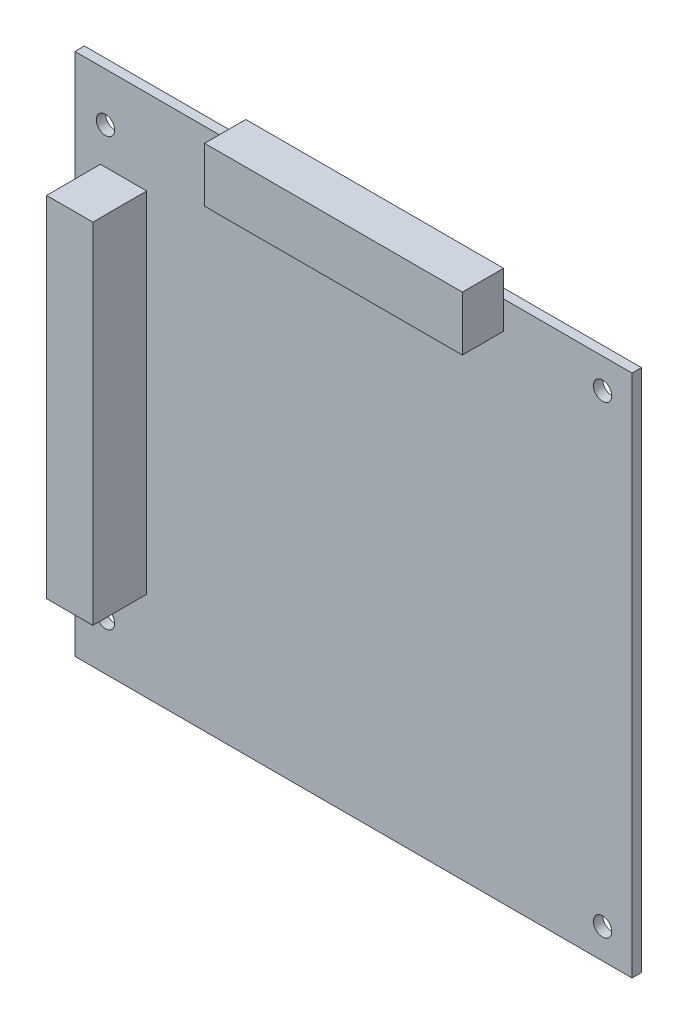
SolidWorks part; units mm, degrees
ref_plane "Front Plane" through (0, 0, 0) normal (0, 0, 1) x (1, 0, 0)
ref_plane "Top Plane" through (0, 0, 0) normal (0, 1, 0) x (1, 0, 0)
ref_plane "Right Plane" through (0, 0, 0) normal (1, 0, 0) x (0, 0, -1)
sketch "Sketch1" plane through (0, 0, 0) normal (0, 0, 1) x (1, 0, 0)
  line L1 (-48.0314, -45.1739) -> (48.0314, -45.1739)
  line L2 (-48.0314, -45.1739) -> (-48.0314, 45.1739)
  line L3 (-48.0314, 45.1739) -> (48.0314, 45.1739)
  line L4 (48.0314, -45.1739) -> (48.0314, 45.1739)
  line L5 (-48.0314, -45.1739) -> (48.0314, 45.1739) construction
  line L6 (-48.0314, 45.1739) -> (48.0314, -45.1739) construction
  point P0 (0, 0)
  dimension "D1" = 96.0628
  dimension "D2" = 90.3478
extrude "PCB" add sketch "Sketch1" along normal blind 1.6256
sketch "Sketch5" plane through (0, 0, 1.6256) normal (0, 0, 1) x (1, 0, 0)
  line L0 (-42.7736, 45.1739) -> (-42.7736, 36.83) construction
  line L1 (48.0314, 45.1739) -> (-48.0314, 45.1739) construction
  line L2 (-42.7736, 36.83) -> (-42.7736, -36.83) construction
  line L3 (-42.7736, -36.83) -> (-42.7736, -45.1739) construction
  line L4 (-48.0314, -45.1739) -> (48.0314, -45.1739) construction
  line L5 (48.0314, -45.1739) -> (48.0314, 45.1739) construction
  line L6 (42.9514, 45.1739) -> (42.9514, 40.005) construction
  line L7 (42.9514, 40.005) -> (42.9514, -40.005) construction
  line L8 (42.9514, -40.005) -> (42.9514, -45.1739) construction
  circle A0 centre (-42.7736, 36.83) radius 1.5875
  circle A1 centre (42.9514, 40.005) radius 1.5875
  circle A2 centre (42.9514, -40.005) radius 1.5875
  circle A3 centre (-42.7736, -36.83) radius 1.5875
  dimension "D5" = 3.175
  dimension "D1" = 73.66
  dimension "D2" = 90.805
  dimension "D3" = 80.01
  dimension "D4" = 5.08
extrude "PCB_Holes" cut sketch "Sketch5" against normal through all
sketch "Sketch2" plane through (0, 0, 1.6256) normal (0, 0, 1) x (1, 0, 0)
  line L0 (-48.0314, 45.1739) -> (-48.0314, -45.1739) construction
  line L1 (-43.6372, 30.5181) -> (-35.6616, 30.5181)
  line L2 (-43.6372, 30.5181) -> (-43.6372, -29.7053)
  line L3 (-43.6372, -29.7053) -> (-35.6616, -29.7053)
  line L4 (-35.6616, 30.5181) -> (-35.6616, -29.7053)
  line L5 (-48.0314, -45.1739) -> (48.0314, -45.1739) construction
  dimension "D1" = 60.2234
  dimension "D2" = 7.9756
  dimension "D3" = 4.3942
  dimension "D4" = 15.4686
extrude "PCI-104_Connector" add sketch "Sketch2" along normal blind 9.2964 and the other way offset from surface (12.6238 mm away) 10.9982 other way up to face at (-41.1861, -36.83, 0)
sketch "Sketch6" plane through (0, 0, 1.6256) normal (0, 0, 1) x (1, 0, 0)
  line L5 (-48.0314, 45.1739) -> (-48.0314, -45.1739) construction
  line L6 (48.0314, 45.1739) -> (-48.0314, 45.1739) construction
  line L7 (-18.5674, 40.3479) -> (25.8826, 40.3479)
  line L8 (-18.5674, 40.3479) -> (-18.5674, 49.7459)
  line L9 (-18.5674, 49.7459) -> (25.8826, 49.7459)
  line L10 (25.8826, 40.3479) -> (25.8826, 49.7459)
  dimension "D5" = 9.398
  dimension "D6" = 44.45
  dimension "D7" = 29.464
  dimension "D8" = 4.572
extrude "PCB_Edge_Conns" add sketch "Sketch6" along normal blind 7.112
